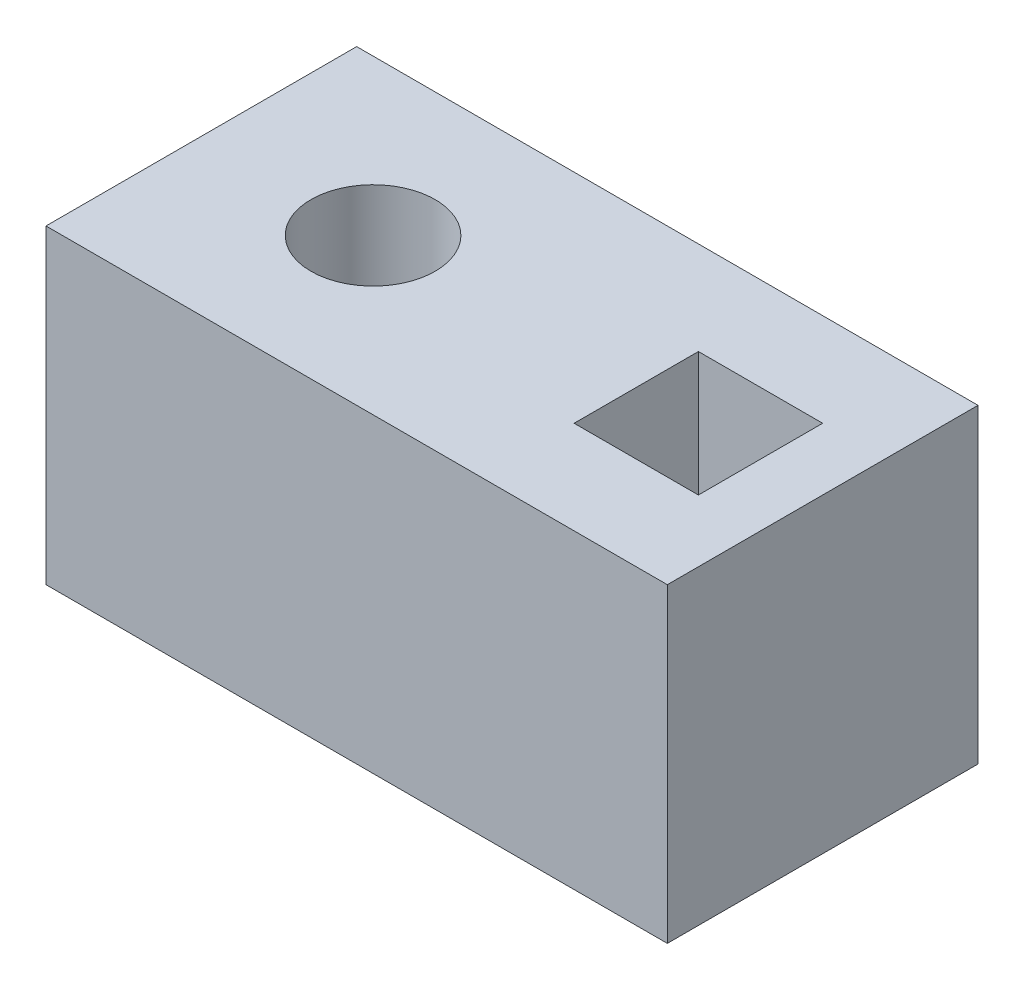
SolidWorks part; units mm, degrees
material "2024 Alloy"
ref_plane "Front Plane" through (0, 0, 0) normal (0, 0, 1) x (1, 0, 0)
ref_plane "Top Plane" through (0, 0, 0) normal (0, 1, 0) x (1, 0, 0)
ref_plane "Right Plane" through (0, 0, 0) normal (1, 0, 0) x (0, 0, -1)
sketch "Sketch1" plane through (0, 0, 0) normal (0, 1, 0) x (1, 0, 0)
  line L0 (-5, 0) -> (5.279, 0) construction
  line L1 (5, -2.5) -> (-5, -2.5)
  line L2 (5, -2.5) -> (5, 2.5)
  line L3 (5, 2.5) -> (-5, 2.5)
  line L4 (-5, -2.5) -> (-5, 2.5)
  line L5 (5, -2.5) -> (-5, 2.5) construction
  line L6 (5, 2.5) -> (-5, -2.5) construction
  line L7 (4, -1) -> (2, -1)
  line L8 (4, -1) -> (4, 1)
  line L9 (4, 1) -> (2, 1)
  line L10 (2, -1) -> (2, 1)
  line L11 (4, -1) -> (2, 1) construction
  line L12 (4, 1) -> (2, -1) construction
  circle A0 centre (-2.2361, 0) radius 1
  point P0 (0, 0)
  point P8 (3, 0)
  point P15 (0, 0)
  point P16 (0, 0)
  point P17 (0, 0)
  dimension "D3" = 2
  dimension "D1" = 2
  dimension "D2" = 2
  dimension "D4" = 10
  dimension "D5" = 5
extrude "Boss-Extrude2" add sketch "Sketch1" along normal blind 5
